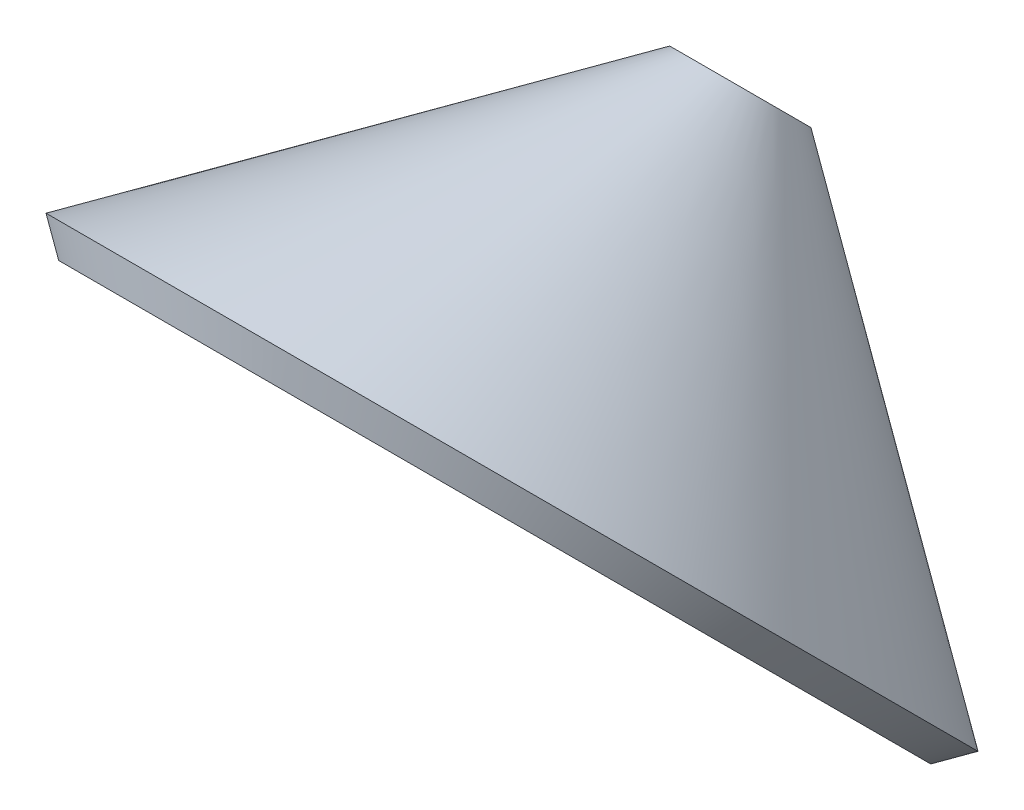
SolidWorks part; units mm, degrees
ref_plane "Plano frontal" through (0, 0, 0) normal (0, 0, 1) x (1, 0, 0)
ref_plane "Plano superior" through (0, 0, 0) normal (0, 1, 0) x (1, 0, 0)
ref_plane "Plano direito" through (0, 0, 0) normal (1, 0, 0) x (0, 0, -1)
sketch "Esboço1" plane through (0, 0, 0) normal (0, 0, 1) x (1, 0, 0)
  line L0 (-11.3481, 23.0346) -> (-1.3481, 23.0346)
  line L1 (-11.3481, 23.0346) -> (-13.3481, 21.0346)
  line L2 (-13.3481, 21.0346) -> (-13.3481, 12.0346)
  line L3 (-13.3481, 12.0346) -> (-7.0343, -0.6266)
  line L4 (-9.719, -4.9654) -> (-9.719, -8.9654)
  line L5 (-9.719, -8.9654) -> (-5.596, -8.9654)
  line L6 (-5.596, -8.9654) -> (-5.596, -32.9654)
  line L7 (-5.596, -32.9654) -> (-1.3481, -32.9654)
  line L8 (-1.3481, -32.9654) -> (-1.3481, 23.0346)
  arc A0 (-7.0343, -0.6266) -> (-9.719, -4.9654) centre (-9.719, -1.9654) cw
  point P7 (0, 0)
  point P12 (0, 0)
  dimension "D3" = 3
  dimension "D1" = 10
  dimension "D2" = 56
  dimension "D4" = 4
  dimension "D5" = 21
  dimension "D6" = 2
  dimension "D7" = 11
  dimension "D8" = 45
sketch "Esboço5" plane through (0, 0, 0) normal (1, 0, 0) x (0, 0, -1)
  line L0 (-4, 28) -> (6, 28)
  line L1 (-4, 28) -> (-6, 26)
  line L2 (-6, 26) -> (-6, 17)
  line L3 (-6, 17) -> (0.3138, 4.3388)
  line L4 (-2.3709, 0) -> (-2.3709, -4)
  line L5 (-2.3709, -4) -> (1.7521, -4)
  line L6 (1.7521, -4) -> (1.7521, -28)
  line L7 (1.7521, -28) -> (6, -28)
  line L8 (6, -28) -> (6, 28)
  arc A0 (0.3138, 4.3388) -> (-2.3709, 0) centre (-2.3709, 3) cw
  dimension "D2" = 3
  dimension "D1" = 10
  dimension "D3" = 4
  dimension "D4" = 21
  dimension "D5" = 11
  dimension "D6" = 2
  dimension "D7" = 45
revolve "Revolução1" add sketch "Esboço5" angle 360 about L1
